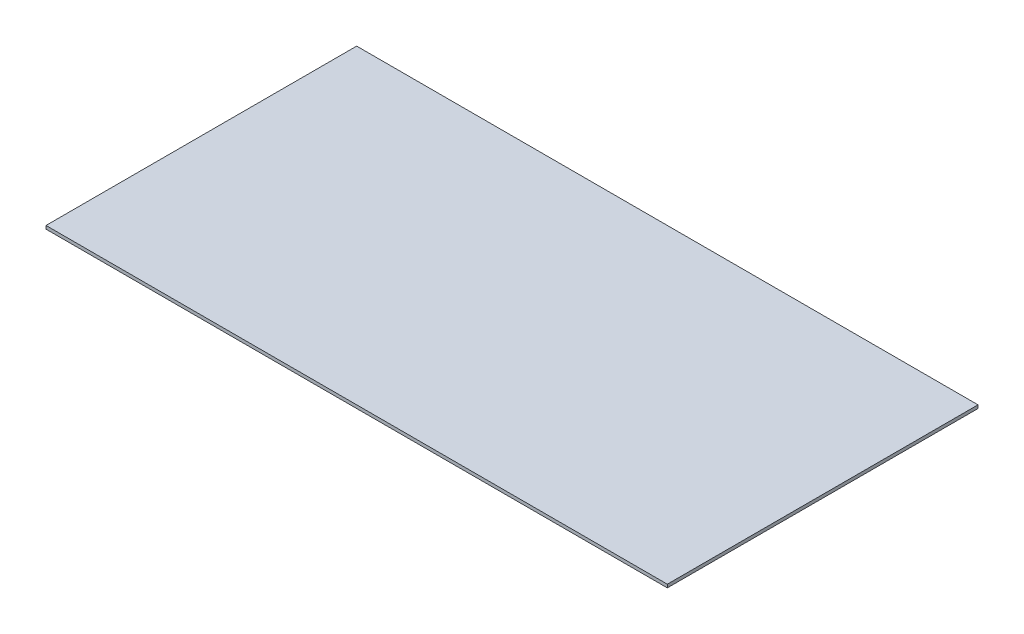
SolidWorks part; units mm, degrees
ref_plane "Front Plane" through (0, 0, 0) normal (0, 0, 1) x (1, 0, 0)
ref_plane "Top Plane" through (0, 0, 0) normal (0, 1, 0) x (1, 0, 0)
ref_plane "Right Plane" through (0, 0, 0) normal (1, 0, 0) x (0, 0, -1)
sketch "Sketch1" plane through (0, 0, 0) normal (0, 1, 0) x (1, 0, 0)
  line L1 (-609.6, -304.8) -> (609.6, -304.8)
  line L2 (-609.6, -304.8) -> (-609.6, 304.8)
  line L3 (-609.6, 304.8) -> (609.6, 304.8)
  line L4 (609.6, -304.8) -> (609.6, 304.8)
  line L5 (-609.6, -304.8) -> (609.6, 304.8) construction
  line L6 (-609.6, 304.8) -> (609.6, -304.8) construction
  point P0 (0, 0)
  dimension "D1" = 1219.2
  dimension "D2" = 609.6
extrude "Boss-Extrude1" add sketch "Sketch1" along normal blind 6.35
